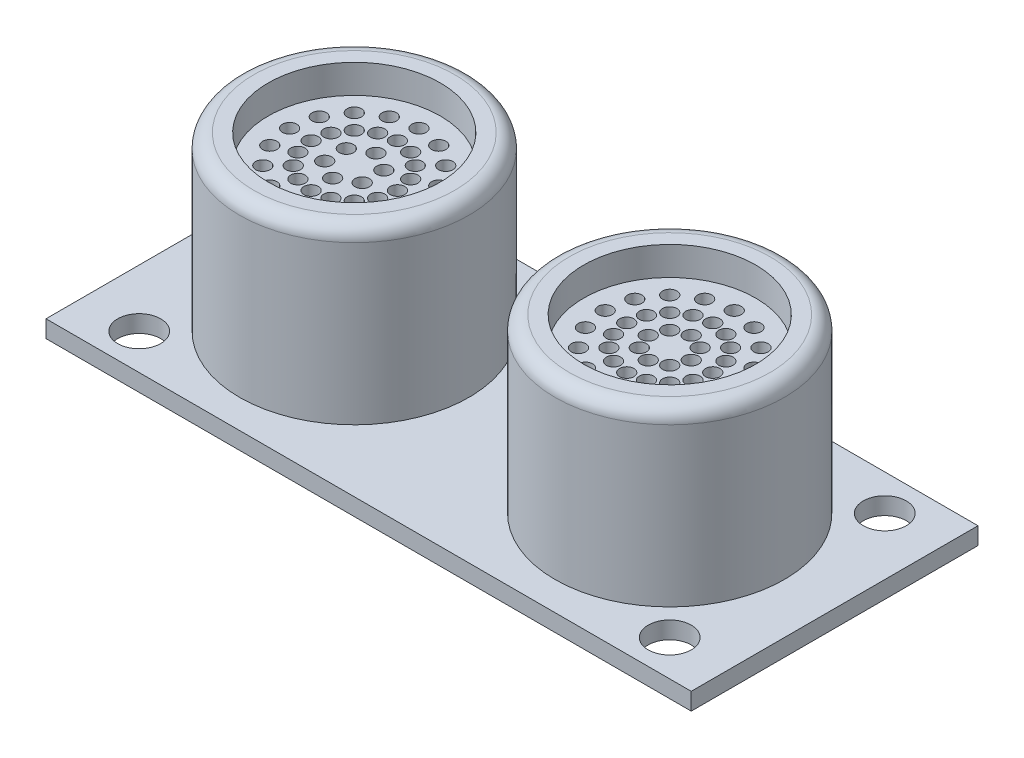
SolidWorks part; units mm, degrees
ref_plane "前视基准面" through (0, 0, 0) normal (0, 0, 1) x (1, 0, 0)
ref_plane "上视基准面" through (0, 0, 0) normal (0, 1, 0) x (1, 0, 0)
ref_plane "右视基准面" through (0, 0, 0) normal (1, 0, 0) x (0, 0, -1)
sketch "草图1" plane through (0, 0, 0) normal (0, 1, 0) x (1, 0, 0)
  line L1 (-22.5, 10) -> (22.5, 10)
  line L2 (-22.5, 10) -> (-22.5, -10)
  line L3 (-22.5, -10) -> (22.5, -10)
  line L4 (22.5, 10) -> (22.5, -10)
  line L5 (-22.5, 10) -> (22.5, -10) construction
  line L6 (-22.5, -10) -> (22.5, 10) construction
  point P0 (0, 0)
  dimension "D1" = 45
  dimension "D2" = 20
extrude "凸台-拉伸1" add sketch "草图1" along normal blind 1.2
ref_plane "基准面1" through (0, 1.2, 0) normal (0, 1, 0) x (1, 0, 0)
sketch "草图2" plane through (0, 1.2, 0) normal (0, 1, 0) x (1, 0, 0)
  line L0 (0, 14.5393) -> (0, -15.016) construction
  circle A0 centre (-11, 0) radius 8
  circle A1 centre (11, 0) radius 8
  circle A2 centre (-11, 0) radius 6
  circle A3 centre (11, 0) radius 6
  dimension "D2" = 16
  dimension "D3" = 16
  dimension "D5" = 12
  dimension "D6" = 12
  dimension "D1" = 22
  dimension "D4" = 11
extrude "凸台-拉伸2" add sketch "草图2" along normal blind 12
fillet "圆角1" radius 1 2 edges at (11, 13.2, 8) (-11, 13.2, 8)
ref_plane "基准面2" through (0, 11.2, 0) normal (0, 1, 0) x (1, 0, 0)
sketch "草图3" plane through (0, 11.2, 0) normal (0, 1, 0) x (1, 0, 0)
  line L0 (-11, 12.7615) -> (-11, -11.9934) construction
  line L1 (-11, -11.9934) -> (-11, 0) construction
  line L2 (-11, 0) -> (-23.9596, 0) construction
  line L3 (-23.9596, 0) -> (23.9491, 0) construction
  line L4 (23.9491, 0) -> (11, 0) construction
  line L5 (11, 0) -> (11, 9.621) construction
  line L6 (11, 9.621) -> (11, -9.5918) construction
  circle A0 centre (-11, 0) radius 6
  circle A1 centre (11, 0) radius 6
  circle A2 centre (-11, 4.5099) radius 0.5
  circle A3 centre (-11, 3.0099) radius 0.5
  circle A4 centre (-11, 1.5099) radius 0.5
  circle A5 centre (-9.2741, 4.1666) radius 0.5
  circle A6 centre (-9.8482, 2.7808) radius 0.5
  circle A7 centre (-7.811, 3.189) radius 0.5
  circle A8 centre (-8.8717, 2.1283) radius 0.5
  circle A9 centre (-6.8334, 1.7259) radius 0.5
  circle A10 centre (-8.2192, 1.1518) radius 0.5
  circle A11 centre (-6.4901, 0) radius 0.5
  circle A12 centre (-7.9901, 0) radius 0.5
  circle A13 centre (-6.8334, -1.7259) radius 0.5
  circle A14 centre (-8.2192, -1.1518) radius 0.5
  circle A15 centre (-7.811, -3.189) radius 0.5
  circle A16 centre (-8.8717, -2.1283) radius 0.5
  circle A17 centre (-9.2741, -4.1666) radius 0.5
  circle A18 centre (-9.8482, -2.7808) radius 0.5
  circle A19 centre (-11, -4.5099) radius 0.5
  circle A20 centre (-11, -3.0099) radius 0.5
  circle A21 centre (-12.7259, -4.1666) radius 0.5
  circle A22 centre (-12.1518, -2.7808) radius 0.5
  circle A23 centre (-14.189, -3.189) radius 0.5
  circle A24 centre (-13.1283, -2.1283) radius 0.5
  circle A25 centre (-15.1666, -1.7259) radius 0.5
  circle A26 centre (-13.7808, -1.1518) radius 0.5
  circle A27 centre (-15.5099, 0) radius 0.5
  circle A28 centre (-14.0099, 0) radius 0.5
  circle A29 centre (-15.1666, 1.7259) radius 0.5
  circle A30 centre (-13.7808, 1.1518) radius 0.5
  circle A31 centre (-14.189, 3.189) radius 0.5
  circle A32 centre (-13.1283, 2.1283) radius 0.5
  circle A33 centre (-12.7259, 4.1666) radius 0.5
  circle A34 centre (-12.1518, 2.7808) radius 0.5
  circle A35 centre (-9.6924, 0.7549) radius 0.5
  circle A36 centre (-9.6924, -0.7549) radius 0.5
  circle A37 centre (-11, -1.5099) radius 0.5
  circle A38 centre (-12.3076, -0.7549) radius 0.5
  circle A39 centre (-12.3076, 0.7549) radius 0.5
  point P82 (-11, 0)
  point P92 (-11, 0)
  dimension "D1" = 1
  dimension "D3" = 1
  dimension "D5" = 1
  dimension "D2" = 4.5099
  dimension "D4" = 1.5
  dimension "D6" = 1.5
  dimension "D7" = 16
  dimension "D8" = 6
extrude "凸台-拉伸3" add sketch "草图3" against normal blind 8
sketch "草图4" plane through (0, 11.2, 0) normal (0, 1, 0) x (1, 0, 0)
  line L0 (0, 12.3512) -> (0, -11.9821) construction
  line L1 (11, 0) -> (11, 8.6973) construction
  line L2 (11, 8.6973) -> (11, -10) construction
  line L3 (-22.5, -10) -> (22.5, -10) construction
  line L4 (11, -10) -> (11, 0) construction
  line L5 (11, 0) -> (2.15, 0) construction
  line L6 (2.15, 0) -> (20.6854, 0) construction
  circle A0 centre (11, 1.5) radius 0.5
  circle A1 centre (11, 3) radius 0.5
  circle A2 centre (11, 4.5) radius 0.5
  circle A3 centre (12.7221, 4.1575) radius 0.5
  circle A4 centre (12.1481, 2.7716) radius 0.5
  circle A5 centre (14.182, 3.182) radius 0.5
  circle A6 centre (13.1213, 2.1213) radius 0.5
  circle A7 centre (15.1575, 1.7221) radius 0.5
  circle A8 centre (13.7716, 1.1481) radius 0.5
  circle A9 centre (15.5, 0) radius 0.5
  circle A10 centre (14, 0) radius 0.5
  circle A11 centre (15.1575, -1.7221) radius 0.5
  circle A12 centre (13.7716, -1.1481) radius 0.5
  circle A13 centre (14.182, -3.182) radius 0.5
  circle A14 centre (13.1213, -2.1213) radius 0.5
  circle A15 centre (12.7221, -4.1575) radius 0.5
  circle A16 centre (12.1481, -2.7716) radius 0.5
  circle A17 centre (11, -4.5) radius 0.5
  circle A18 centre (11, -3) radius 0.5
  circle A19 centre (9.2779, -4.1575) radius 0.5
  circle A20 centre (9.8519, -2.7716) radius 0.5
  circle A21 centre (7.818, -3.182) radius 0.5
  circle A22 centre (8.8787, -2.1213) radius 0.5
  circle A23 centre (6.8425, -1.7221) radius 0.5
  circle A24 centre (8.2284, -1.1481) radius 0.5
  circle A25 centre (6.5, 0) radius 0.5
  circle A26 centre (8, 0) radius 0.5
  circle A27 centre (6.8425, 1.7221) radius 0.5
  circle A28 centre (8.2284, 1.1481) radius 0.5
  circle A29 centre (7.818, 3.182) radius 0.5
  circle A30 centre (8.8787, 2.1213) radius 0.5
  circle A31 centre (9.2779, 4.1575) radius 0.5
  circle A32 centre (9.8519, 2.7716) radius 0.5
  circle A33 centre (12.0607, 1.0607) radius 0.5
  circle A34 centre (12.5, 0) radius 0.5
  circle A35 centre (12.0607, -1.0607) radius 0.5
  circle A36 centre (11, -1.5) radius 0.5
  circle A37 centre (9.9393, -1.0607) radius 0.5
  circle A38 centre (9.5, 0) radius 0.5
  circle A39 centre (9.9393, 1.0607) radius 0.5
  point P81 (11, 0)
  point P95 (11, 0)
  dimension "D4" = 1
  dimension "D5" = 1
  dimension "D6" = 1
  dimension "D1" = 1.5
  dimension "D2" = 1.5
  dimension "D3" = 1.5
  dimension "D7" = 16
  dimension "D8" = 8
extrude "切除-拉伸1" cut sketch "草图4" against normal blind 8
sketch "草图5" plane through (0, 1.2, 0) normal (0, 1, 0) x (1, 0, 0)
  line L0 (0, 10) -> (0, 20.3974) construction
  line L1 (22.5, 10) -> (-22.5, 10) construction
  line L2 (0, 20.3974) -> (0, -22.8929) construction
  line L3 (-28.3933, 0) -> (25.4886, 0) construction
  circle A0 centre (-18.5, 7.5) radius 1.5
  circle A6 centre (-18.5, -7.5) radius 1.5
  circle A7 centre (18.5, -7.5) radius 1.5
  circle A8 centre (18.5, 7.5) radius 1.5
  dimension "D3" = 3
  dimension "D1" = 18.5
  dimension "D2" = 7.5
extrude "切除-拉伸2" cut sketch "草图5" against normal through all
